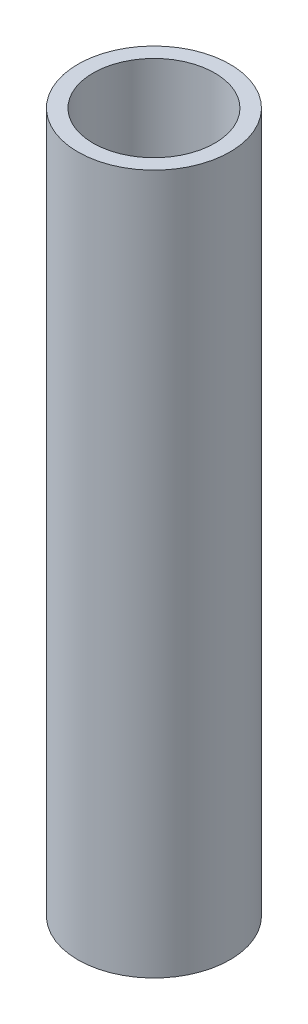
SolidWorks part; units mm, degrees
ref_plane "Front" through (0, 0, 0) normal (0, 0, 1) x (1, 0, 0)
ref_plane "Top" through (0, 0, 0) normal (0, 1, 0) x (1, 0, 0)
ref_plane "Right" through (0, 0, 0) normal (1, 0, 0) x (0, 0, -1)
sketch "Sketch1" plane through (0, 0, 0) normal (0, 1, 0) x (1, 0, 0)
  circle A0 centre (0, 0) radius 15.875
  circle A1 centre (0, 0) radius 12.7
  dimension "D1" = 31.75
  dimension "D2" = 3.175
extrude "Boss-Extrude1" add sketch "Sketch1" along normal mid plane 146.05
